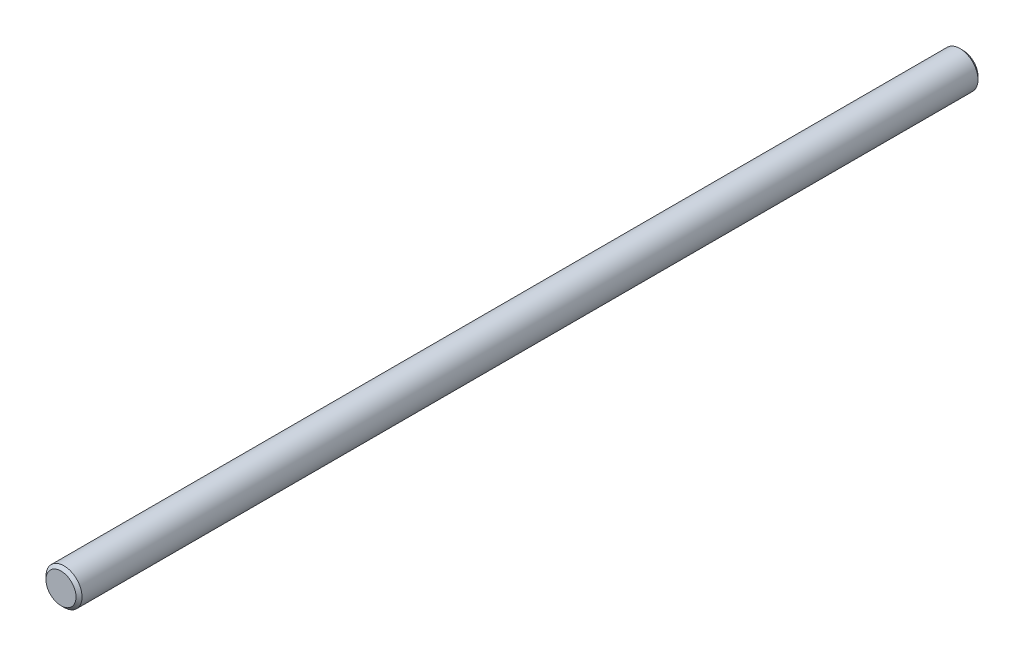
SolidWorks part; units mm, degrees
ref_plane "Alzado" through (0, 0, 0) normal (0, 0, 1) x (1, 0, 0)
ref_plane "Planta" through (0, 0, 0) normal (0, 1, 0) x (1, 0, 0)
ref_plane "Vista lateral" through (0, 0, 0) normal (1, 0, 0) x (0, 0, -1)
sketch "Croquis1" plane through (0, 0, 0) normal (0, 0, 1) x (1, 0, 0)
  circle A0 centre (0, 0) radius 6
  dimension "D1" = 12
extrude "Saliente-Extruir1" add sketch "Croquis1" along normal blind 300 contours A0
chamfer "Chaflán1" distance 1 angle 45 2 edges at (6, 0, 0) (6, 0, 300)
